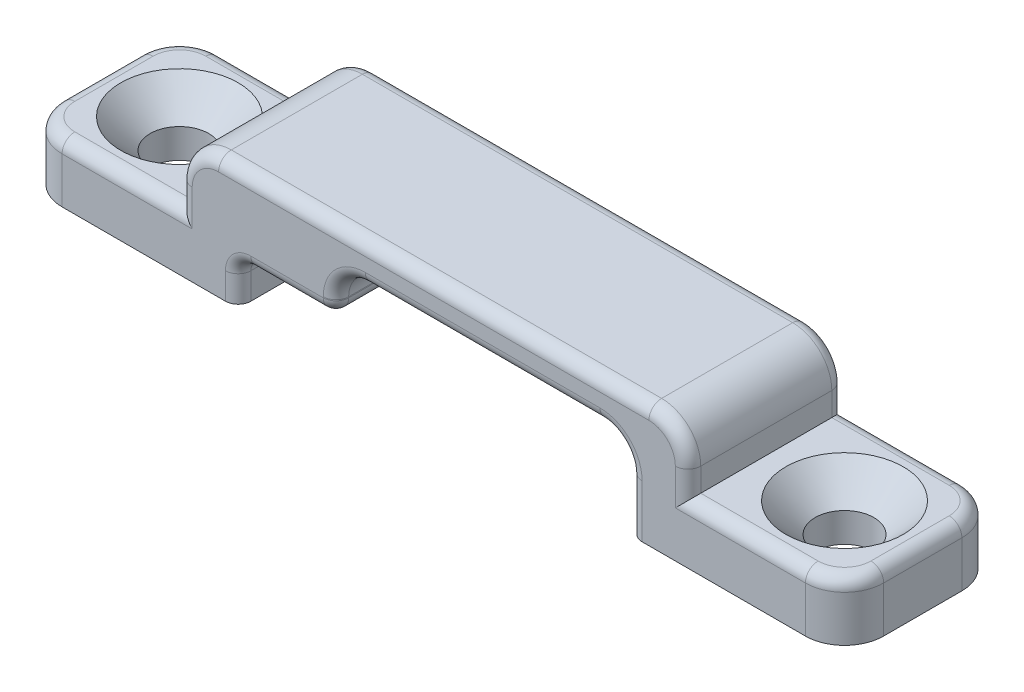
SolidWorks part; units mm, degrees
ref_plane "Plano frontal" through (0, 0, 0) normal (0, 0, 1) x (1, 0, 0)
ref_plane "Plano superior" through (0, 0, 0) normal (0, 1, 0) x (1, 0, 0)
ref_plane "Plano direito" through (0, 0, 0) normal (1, 0, 0) x (0, 0, -1)
sketch "Esboço1" plane through (0, 0, 0) normal (0, 0, 1) x (1, 0, 0)
  line L1 (-11.5, -1.2) -> (-11.5, 1.8)
  line L2 (-11.5, 1.8) -> (-3.5, 1.8)
  line L3 (-3.5, 1.8) -> (-3.5, 5)
  line L4 (-3.5, 5) -> (22.5, 5)
  line L5 (22.5, 5) -> (22.5, 1.8)
  line L9 (-11.5, -1.2) -> (-0.5, -1.2)
  line L10 (-0.5, -1.2) -> (-0.5, 0.8)
  line L12 (30.5, -1.2) -> (19.5, -1.2)
  line L13 (19.5, -1.2) -> (19.5, 3)
  line L14 (4.5, 3) -> (19.5, 3)
  line L15 (22.5, 1.8) -> (30.5, 1.8)
  line L16 (30.5, 1.8) -> (30.5, -1.2)
  line L17 (-5.3215, -1.2) -> (15.1676, -1.2) construction
  line L18 (4.5, -1.2) -> (-0.5, -1.2) construction
  line L19 (4.5, -1.2) -> (4.5, 0.8) construction
  line L20 (4.5, 0.8) -> (-0.5, 0.8) construction
  line L21 (-0.5, -1.2) -> (-0.5, 0.8) construction
  line L22 (-0.5, 0.8) -> (4.5, 0.8)
  line L23 (4.5, 0.8) -> (4.5, 3)
  circle A0 centre (7, 1.3) radius 2.5 construction
  circle A1 centre (11.8477, 1.15) radius 2.35 construction
  circle A2 centre (16.2907, 0.9) radius 2.1 construction
  dimension "D1" = 3
  dimension "D7" = 3
  dimension "D12" = 5
  dimension "D13" = 4.7
  dimension "D14" = 4.2
  dimension "D2" = 3
  dimension "D3" = 8
  dimension "D4" = 2
  dimension "D5" = 4.2
  dimension "D6" = 20
  dimension "D8" = 3
  dimension "D9" = 8
  dimension "D10" = 2
  dimension "D11" = 5
extrude "Ressalto-extrusão1" add sketch "Esboço1" along normal blind 8
sketch "Esboço2" plane through (0, 1.8, 0) normal (0, 1, 0) x (1, 0, 0)
  line L0 (-3.5, -8) -> (-11.5, 0) construction
  line L3 (22.5, -8) -> (30.5, 0) construction
  circle A0 centre (-7.5, -4) radius 1.5
  circle A1 centre (26.5, -4) radius 1.5
  point P8 (-11.5, 0)
  point P9 (-3.5, -8)
  point P10 (30.5, 0)
  point P11 (23.8255, -6.9007)
  point P12 (22.5, -8)
  dimension "D1" = 3
  dimension "D2" = 3
extrude "Corte-extrusão1" cut sketch "Esboço2" against normal blind 6
chamfer "Chanfro2" distance 1.5 angle 45 2 edges at (-9, 1.8, 4) (25, 1.8, 4)
fillet "Filete1" radius 2 6 edges at (30.5, 0.3, 0) (30.5, 0.3, 8) (22.5, 5, 4) (-3.5, 5, 4) (-11.5, 0.3, 0) (-11.5, 0.3, 8)
fillet "Filete2" radius 1.5 2 edges at (19.5, 3, 4) (4.5, 3, 4)
fillet "Filete3" radius 0.65 36 edges at (-0.5, -0.2, 8) (19.5, 0.15, 8) (19.0607, 2.5607, 8) (-0.5, -0.2, 0) (19.5, 0.15, 0) (19.0607, 2.5607, 0) (22.5, 2.4, 0) (21.9142, 4.4142, 0) (-3.5, 2.4, 0) (-2.9142, 4.4142, 0) (25.5, 1.8, 0) (29.9142, 1.8, 0.5858) (30.5, 1.8, 4) (29.9142, 1.8, 7.4142) (22.5, 2.4, 8) (21.9142, 4.4142, 8) (-3.5, 2.4, 8) (-2.9142, 4.4142, 8) (-6.5, 1.8, 0) (-10.9142, 1.8, 0.5858) (-11.5, 1.8, 4) (-10.9142, 1.8, 7.4142) (12, 3, 8) (12, 3, 0) (9.5, 5, 0) (25.5, 1.8, 8) (9.5, 5, 8) (-6.5, 1.8, 8) (4.5, 1.15, 8) (4.9393, 2.5607, 8) (4.5, 1.15, 0) (4.9393, 2.5607, 0) (-0.5, 0.8, 4) (4.5, 0.8, 4) (2, 0.8, 0) (2, 0.8, 8)
